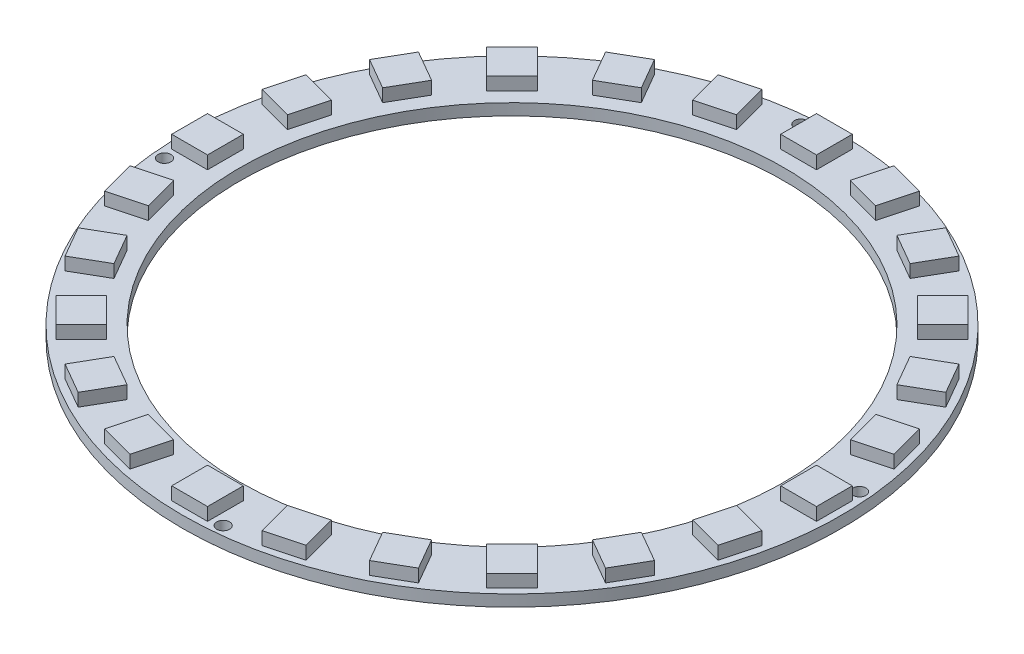
SolidWorks part; units mm, degrees
ref_plane "Plan de face" through (0, 0, 0) normal (0, 0, 1) x (1, 0, 0)
ref_plane "Plan de dessus" through (0, 0, 0) normal (0, 1, 0) x (1, 0, 0)
ref_plane "Plan de droite" through (0, 0, 0) normal (1, 0, 0) x (0, 0, -1)
sketch "Esquisse1" plane through (0, 0, 0) normal (0, 1, 0) x (1, 0, 0)
  circle A0 centre (0, 0) radius 38
  circle A1 centre (0, 0) radius 46
  dimension "D1" = 92
  dimension "D2" = 76
extrude "Boss.-Extru.1" add sketch "Esquisse1" along normal blind 1.6
sketch "Esquisse2" plane through (0, 1.6, 0) normal (0, 1, 0) x (1, 0, 0)
  line L0 (-4.0949, 44.4116) -> (-4.2235, 45.8057) construction
  circle A0 centre (-4.0949, 44.4116) radius 0.9
  circle A1 centre (0, 0) radius 46 construction
  circle A2 centre (44.4116, 4.0949) radius 0.9
  circle A3 centre (4.0949, -44.4116) radius 0.9
  circle A4 centre (-44.4116, -4.0949) radius 0.9
  point P4 (0, 0)
  point P8 (-5.7219, 44.2536)
  point P9 (-4.879, 44.3323)
  point P16 (0, 0)
  point P17 (-4.0949, 44.4116)
  dimension "D1" = 1.8
  dimension "D2" = 1.4
  dimension "D3" = 4
extrude "Enlèv. mat.-Extru.1" cut sketch "Esquisse2" against normal blind 1.6
sketch "Esquisse3" plane through (0, 1.6, 0) normal (0, 1, 0) x (1, 0, 0)
  line L0 (0, 40) -> (0, 38) construction
  line L1 (-2.5, 45) -> (2.5, 45)
  line L2 (-2.5, 45) -> (-2.5, 40)
  line L3 (-2.5, 40) -> (2.5, 40)
  line L4 (2.5, 45) -> (2.5, 40)
  line L5 (9.232, 44.1137) -> (14.0617, 42.8196)
  line L6 (9.232, 44.1137) -> (7.9379, 39.2841)
  line L7 (7.9379, 39.2841) -> (12.7676, 37.99)
  line L8 (14.0617, 42.8196) -> (12.7676, 37.99)
  line L9 (20.3349, 40.2211) -> (24.6651, 37.7211)
  line L10 (20.3349, 40.2211) -> (17.8349, 35.891)
  line L11 (17.8349, 35.891) -> (22.1651, 33.391)
  line L12 (24.6651, 37.7211) -> (22.1651, 33.391)
  line L13 (30.052, 33.5876) -> (33.5876, 30.052)
  line L14 (30.052, 33.5876) -> (26.5165, 30.052)
  line L15 (26.5165, 30.052) -> (30.052, 26.5165)
  line L16 (33.5876, 30.052) -> (30.052, 26.5165)
  line L17 (37.7211, 24.6651) -> (40.2211, 20.3349)
  line L18 (37.7211, 24.6651) -> (33.391, 22.1651)
  line L19 (33.391, 22.1651) -> (35.891, 17.8349)
  line L20 (40.2211, 20.3349) -> (35.891, 17.8349)
  line L21 (42.8196, 14.0617) -> (44.1137, 9.232)
  line L22 (42.8196, 14.0617) -> (37.99, 12.7676)
  line L23 (37.99, 12.7676) -> (39.2841, 7.9379)
  line L24 (44.1137, 9.232) -> (39.2841, 7.9379)
  line L25 (45, 2.5) -> (45, -2.5)
  line L26 (45, 2.5) -> (40, 2.5)
  line L27 (40, 2.5) -> (40, -2.5)
  line L28 (45, -2.5) -> (40, -2.5)
  line L29 (44.1137, -9.232) -> (42.8196, -14.0617)
  line L30 (44.1137, -9.232) -> (39.2841, -7.9379)
  line L31 (39.2841, -7.9379) -> (37.99, -12.7676)
  line L32 (42.8196, -14.0617) -> (37.99, -12.7676)
  line L33 (40.2211, -20.3349) -> (37.7211, -24.6651)
  line L34 (40.2211, -20.3349) -> (35.891, -17.8349)
  line L35 (35.891, -17.8349) -> (33.391, -22.1651)
  line L36 (37.7211, -24.6651) -> (33.391, -22.1651)
  line L37 (33.5876, -30.052) -> (30.052, -33.5876)
  line L38 (33.5876, -30.052) -> (30.052, -26.5165)
  line L39 (30.052, -26.5165) -> (26.5165, -30.052)
  line L40 (30.052, -33.5876) -> (26.5165, -30.052)
  line L41 (24.6651, -37.7211) -> (20.3349, -40.2211)
  line L42 (24.6651, -37.7211) -> (22.1651, -33.391)
  line L43 (22.1651, -33.391) -> (17.8349, -35.891)
  line L44 (20.3349, -40.2211) -> (17.8349, -35.891)
  line L45 (14.0617, -42.8196) -> (9.232, -44.1137)
  line L46 (14.0617, -42.8196) -> (12.7676, -37.99)
  line L47 (12.7676, -37.99) -> (7.9379, -39.2841)
  line L48 (9.232, -44.1137) -> (7.9379, -39.2841)
  line L49 (2.5, -45) -> (-2.5, -45)
  line L50 (2.5, -45) -> (2.5, -40)
  line L51 (2.5, -40) -> (-2.5, -40)
  line L52 (-2.5, -45) -> (-2.5, -40)
  line L53 (-9.232, -44.1137) -> (-14.0617, -42.8196)
  line L54 (-9.232, -44.1137) -> (-7.9379, -39.2841)
  line L55 (-7.9379, -39.2841) -> (-12.7676, -37.99)
  line L56 (-14.0617, -42.8196) -> (-12.7676, -37.99)
  line L57 (-20.3349, -40.2211) -> (-24.6651, -37.7211)
  line L58 (-20.3349, -40.2211) -> (-17.8349, -35.891)
  line L59 (-17.8349, -35.891) -> (-22.1651, -33.391)
  line L60 (-24.6651, -37.7211) -> (-22.1651, -33.391)
  line L61 (-30.052, -33.5876) -> (-33.5876, -30.052)
  line L62 (-30.052, -33.5876) -> (-26.5165, -30.052)
  line L63 (-26.5165, -30.052) -> (-30.052, -26.5165)
  line L64 (-33.5876, -30.052) -> (-30.052, -26.5165)
  line L65 (-37.7211, -24.6651) -> (-40.2211, -20.3349)
  line L66 (-37.7211, -24.6651) -> (-33.391, -22.1651)
  line L67 (-33.391, -22.1651) -> (-35.891, -17.8349)
  line L68 (-40.2211, -20.3349) -> (-35.891, -17.8349)
  line L69 (-42.8196, -14.0617) -> (-44.1137, -9.232)
  line L70 (-42.8196, -14.0617) -> (-37.99, -12.7676)
  line L71 (-37.99, -12.7676) -> (-39.2841, -7.9379)
  line L72 (-44.1137, -9.232) -> (-39.2841, -7.9379)
  line L73 (-45, -2.5) -> (-45, 2.5)
  line L74 (-45, -2.5) -> (-40, -2.5)
  line L75 (-40, -2.5) -> (-40, 2.5)
  line L76 (-45, 2.5) -> (-40, 2.5)
  line L77 (-44.1137, 9.232) -> (-42.8196, 14.0617)
  line L78 (-44.1137, 9.232) -> (-39.2841, 7.9379)
  line L79 (-39.2841, 7.9379) -> (-37.99, 12.7676)
  line L80 (-42.8196, 14.0617) -> (-37.99, 12.7676)
  line L81 (-40.2211, 20.3349) -> (-37.7211, 24.6651)
  line L82 (-40.2211, 20.3349) -> (-35.891, 17.8349)
  line L83 (-35.891, 17.8349) -> (-33.391, 22.1651)
  line L84 (-37.7211, 24.6651) -> (-33.391, 22.1651)
  line L85 (-33.5876, 30.052) -> (-30.052, 33.5876)
  line L86 (-33.5876, 30.052) -> (-30.052, 26.5165)
  line L87 (-30.052, 26.5165) -> (-26.5165, 30.052)
  line L88 (-30.052, 33.5876) -> (-26.5165, 30.052)
  line L89 (-24.6651, 37.7211) -> (-20.3349, 40.2211)
  line L90 (-24.6651, 37.7211) -> (-22.1651, 33.391)
  line L91 (-22.1651, 33.391) -> (-17.8349, 35.891)
  line L92 (-20.3349, 40.2211) -> (-17.8349, 35.891)
  line L93 (-14.0617, 42.8196) -> (-9.232, 44.1137)
  line L94 (-14.0617, 42.8196) -> (-12.7676, 37.99)
  line L95 (-12.7676, 37.99) -> (-7.9379, 39.2841)
  line L96 (-9.232, 44.1137) -> (-7.9379, 39.2841)
  circle A0 centre (0, 0) radius 38 construction
  point P104 (0, 0)
  dimension "D1" = 5
  dimension "D2" = 5
  dimension "D3" = 2
  dimension "D4" = 24
extrude "Boss.-Extru.2" add sketch "Esquisse3" along normal blind 1.8
